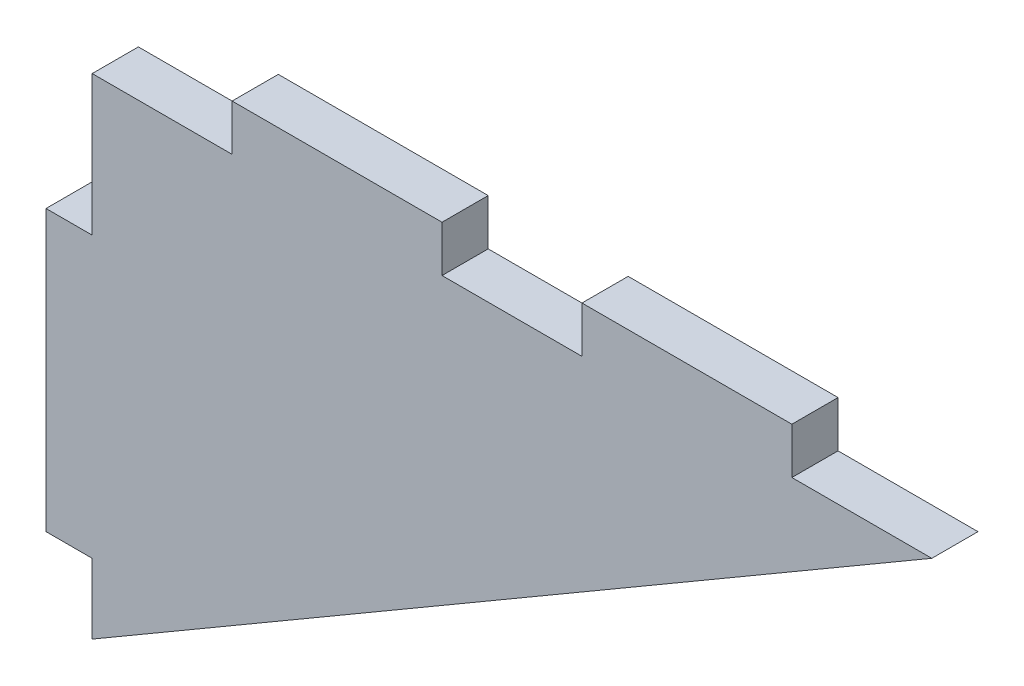
SolidWorks part; units mm, degrees
material "Pine"
ref_plane "Front Plane" through (0, 0, 0) normal (0, 0, 1) x (1, 0, 0)
ref_plane "Top Plane" through (0, 0, 0) normal (0, 1, 0) x (1, 0, 0)
ref_plane "Right Plane" through (0, 0, 0) normal (1, 0, 0) x (0, 0, -1)
sketch "Sketch1" plane through (0, 0, 0) normal (0, 0, 1) x (1, 0, 0)
  line L0 (-30, -17.5) -> (30, 17.5)
  line L5 (-30, 17.5) -> (53.4117, -31.1568) construction
  line L6 (-30, -17.5) -> (30, 17.5) construction
  line L7 (-30, -12.5) -> (-33.3, -12.5)
  line L8 (-33.3, -12.5) -> (-33.3, 7.5)
  line L9 (-33.3, 7.5) -> (-30, 7.5)
  line L10 (-20, 17.5) -> (-20, 20.8)
  line L11 (-20, 20.8) -> (-5, 20.8)
  line L12 (-5, 20.8) -> (-5, 17.5)
  line L13 (5, 17.5) -> (5, 20.8)
  line L14 (5, 20.8) -> (20, 20.8)
  line L15 (20, 20.8) -> (20, 17.5)
  line L16 (-30, 7.5) -> (-30, 17.5)
  line L17 (-30, -12.5) -> (-30, -17.5)
  line L18 (-30, 17.5) -> (-20, 17.5)
  line L19 (-5, 17.5) -> (5, 17.5)
  line L20 (20, 17.5) -> (30, 17.5)
  point P0 (0, 0)
  dimension "D1" = 35
  dimension "D2" = 17.5
  dimension "D3" = 20
  dimension "D4" = 10
  dimension "D5" = 10
  dimension "D6" = 30
  dimension "D7" = 10
  dimension "D8" = 15
  dimension "D9" = 3.3
extrude "Boss-Extrude1" add sketch "Sketch1" along normal blind 3.3
